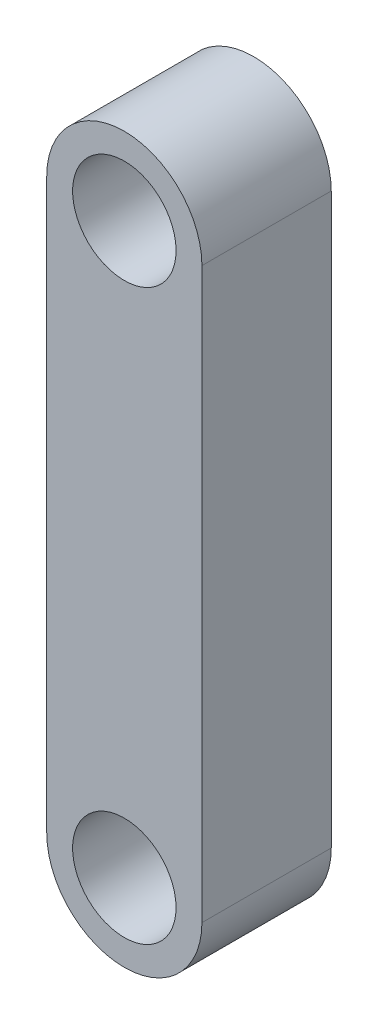
SolidWorks part; units mm, degrees
ref_plane "Front Plane" through (0, 0, 0) normal (0, 0, 1) x (1, 0, 0)
ref_plane "Top Plane" through (0, 0, 0) normal (0, 1, 0) x (1, 0, 0)
ref_plane "Right Plane" through (0, 0, 0) normal (1, 0, 0) x (0, 0, -1)
sketch "Sketch1" plane through (0, 0, 0) normal (0, 0, 1) x (1, 0, 0)
  line L0 (-1.2348, 17.0731) -> (-1.2348, -4.9269)
  line L1 (4.7652, 17.0731) -> (4.7652, -4.9269)
  arc A0 (-1.2348, 17.0731) -> (4.7652, 17.0731) centre (1.7652, 17.0731) cw
  arc A1 (-1.2348, -4.9269) -> (4.7652, -4.9269) centre (1.7652, -4.9269) ccw
  circle A2 centre (1.7652, 17.0731) radius 2
  circle A3 centre (1.7652, -4.9269) radius 2
  dimension "D3" = 4
  dimension "D4" = 4
  dimension "D1" = 22
  dimension "D2" = 6
extrude "Boss-Extrude1" add sketch "Sketch1" along normal blind 5
